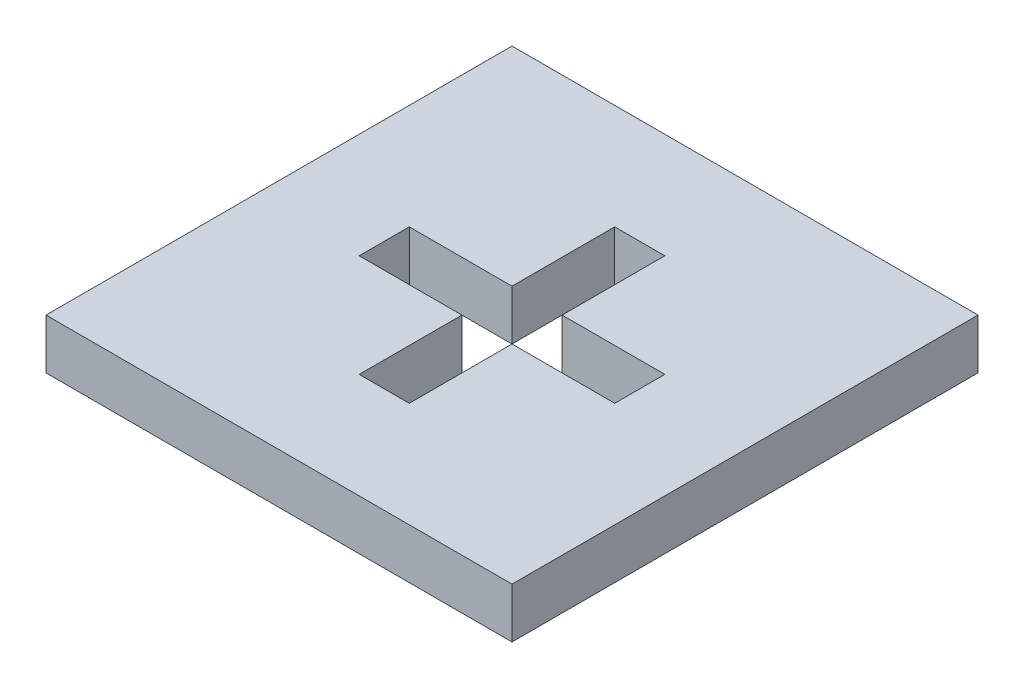
SolidWorks part; units mm, degrees
material "Pine"
ref_plane "Front Plane" through (0, 0, 0) normal (0, 0, 1) x (1, 0, 0)
ref_plane "Top Plane" through (0, 0, 0) normal (0, 1, 0) x (1, 0, 0)
ref_plane "Right Plane" through (0, 0, 0) normal (1, 0, 0) x (0, 0, -1)
sketch "Sketch1" plane through (0, 0, 0) normal (0, 1, 0) x (1, 0, 0)
  line L1 (0, 0) -> (50.8, 0)
  line L2 (0, 0) -> (0, 50.8)
  line L3 (0, 50.8) -> (50.8, 50.8)
  line L4 (50.8, 0) -> (50.8, 50.8)
  line L5 (25.4, 50.8) -> (25.4, 0) construction
  line L6 (0, 25.4) -> (50.8, 25.4) construction
  point P80 (25.4, 25.4)
  dimension "D1" = 50.8
extrude "Boss-Extrude1" add sketch "Sketch1" along normal blind 5.461
sketch "Sketch2" plane through (0, 5.461, 0) normal (0, 1, 0) x (1, 0, 0)
  line L0 (11.4723, 50.8) -> (11.4723, 0) construction
  line L3 (50.8, 50.8) -> (0, 50.8) construction
  line L11 (0, 0) -> (50.8, 0) construction
  line L12 (0, 50.8) -> (0, 0) construction
  line L17 (0, 11.4723) -> (50.8, 11.4723) construction
  line L18 (50.8, 0) -> (50.8, 50.8) construction
  line L22 (39.3277, 50.8) -> (39.3277, 0) construction
  line L23 (0, 39.3277) -> (50.8, 39.3277) construction
  line L24 (25.4, 39.3277) -> (25.4, 11.4723) construction
  line L25 (11.4723, 25.4) -> (39.3277, 25.4) construction
  line L26 (28.1305, 28.1305) -> (39.3277, 28.1305)
  line L27 (22.6695, 39.3277) -> (28.1305, 39.3277)
  line L28 (22.6695, 39.3277) -> (22.6695, 28.1305)
  line L29 (22.6695, 11.4723) -> (28.1305, 11.4723)
  line L30 (28.1305, 39.3277) -> (28.1305, 28.1305)
  line L31 (25.4, 11.4723) -> (25.4, 39.3277) construction
  line L32 (22.225, 25.4) -> (28.575, 25.4) construction
  line L33 (11.4723, 28.1305) -> (22.6695, 28.1305)
  line L34 (11.4723, 28.1305) -> (11.4723, 22.6695)
  line L35 (11.4723, 22.6695) -> (22.6695, 22.6695)
  line L36 (39.3277, 28.1305) -> (39.3277, 22.6695)
  line L37 (25.4, 22.225) -> (25.4, 28.575) construction
  line L38 (11.4723, 25.4) -> (39.3277, 25.4) construction
  line L39 (28.1305, 22.6695) -> (39.3277, 22.6695)
  line L40 (28.1305, 22.6695) -> (28.1305, 11.4723)
  line L41 (22.6695, 22.6695) -> (22.6695, 11.4723)
  point P240 (25.4, 25.4)
  point P531 (25.4, 25.4)
  dimension "D1" = 11.4723
  dimension "D2" = 11.4723
  dimension "D3" = 11.4723
  dimension "D4" = 11.4723
  dimension "D5" = 5.461
  dimension "D6" = 5.461
extrude "Cut-Extrude1" cut sketch "Sketch2" against normal blind 5.461
equation "\"Stock Thickness\"= .215in"
equation "\"D1@Boss-Extrude1\"=\"Stock Thickness\""
equation "\"D1@Cut-Extrude1\"=\"Stock Thickness\""
equation "\"D1@Sketch2\"=\"D1@Sketch1\"/3 - \"Stock Thickness\""
equation "\"D2@Sketch2\"=\"D1@Sketch1\"/3 - \"Stock Thickness\""
equation "\"D3@Sketch2\"=\"D2@Sketch2\""
equation "\"D4@Sketch2\"=\"D1@Sketch2\""
equation "\"D5@Sketch2\"=\"Stock Thickness\""
equation "\"D6@Sketch2\"=\"Stock Thickness\""
